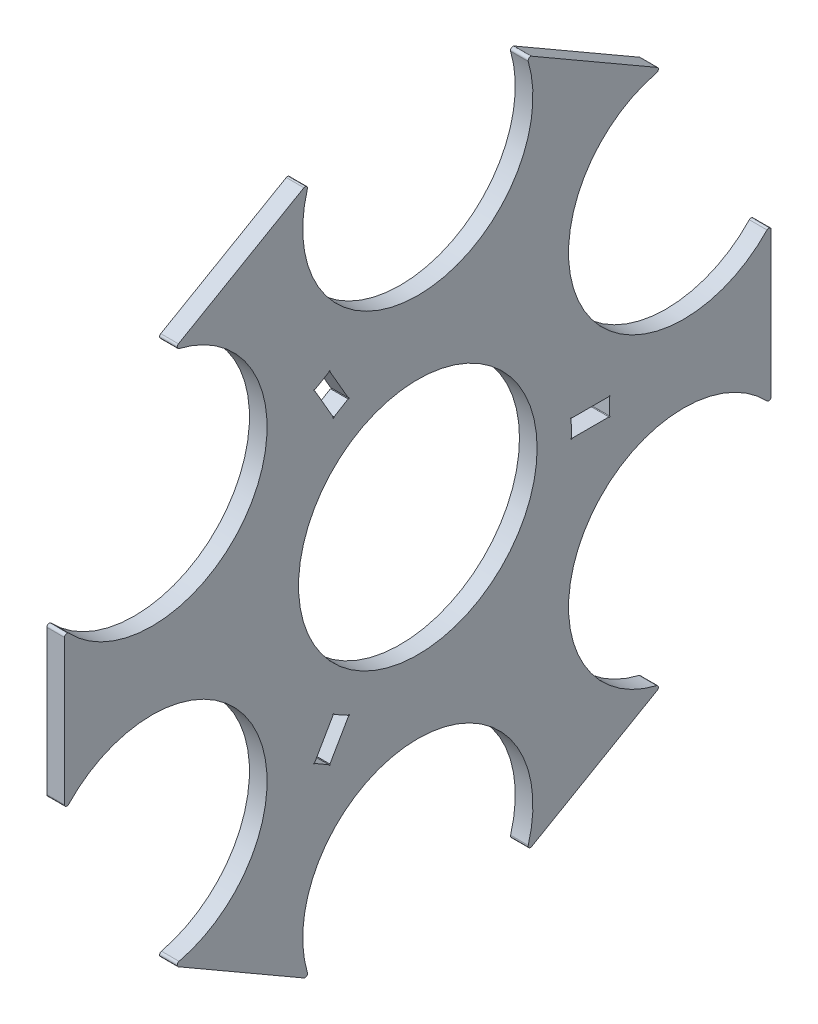
SolidWorks part; units mm, degrees
ref_plane "Front Plane" through (0, 0, 0) normal (0, 0, 1) x (1, 0, 0)
ref_plane "Top Plane" through (0, 0, 0) normal (0, 1, 0) x (1, 0, 0)
ref_plane "Right Plane" through (0, 0, 0) normal (1, 0, 0) x (0, 0, -1)
sketch "Sketch2" plane through (0, 0, 0) normal (1, 0, 0) x (0, 0, -1)
  line L0 (35.921, 114.3) -> (-35.921, 114.3) construction
  line L1 (81.0262, 88.2585) -> (35.921, 114.3)
  line L2 (116.9472, -26.0415) -> (116.9472, 26.0415)
  line L3 (35.921, -114.3) -> (81.0262, -88.2585)
  line L4 (-81.0262, -88.2585) -> (-35.921, -114.3)
  line L5 (-116.9472, 26.0415) -> (-116.9472, -26.0415)
  line L6 (-35.921, 114.3) -> (-81.0262, 88.2585)
  circle A0 centre (0, 0) radius 101.6 construction
  arc A1 (-35.921, 114.3) -> (35.921, 114.3) centre (0, 101.6) ccw
  arc A2 (81.0262, 88.2585) -> (116.9472, 26.0415) centre (87.9882, 50.8) ccw
  arc A3 (116.9472, -26.0415) -> (81.0262, -88.2585) centre (87.9882, -50.8) ccw
  arc A4 (35.921, -114.3) -> (-35.921, -114.3) centre (0, -101.6) ccw
  arc A5 (-81.0262, -88.2585) -> (-116.9472, -26.0415) centre (-87.9882, -50.8) ccw
  arc A6 (-116.9472, 26.0415) -> (-81.0262, 88.2585) centre (-87.9882, 50.8) ccw
  circle A7 centre (0, 0) radius 39.4875
  point P23 (0, 0)
  point P34 (0, 0)
  dimension "D1" = 203.2
  dimension "D2" = 114.3
  dimension "D3" = 76.2
  dimension "D6" = 78.9749
  dimension "D4" = 6
  dimension "D5" = 6
extrude "Boss-Extrude1" add sketch "Sketch2" along normal blind 5.842
fillet "Fillet1" radius 0.7937 12 edges at (2.921, -114.3, 35.921) (2.921, -114.3, -35.921) (2.921, -88.2585, -81.0262) (2.921, -26.0415, -116.9472) (2.921, 88.2585, -81.0262) (2.921, 26.0415, -116.9472) (2.921, -88.2585, 81.0262) (2.921, -26.0415, 116.9472) (2.921, 26.0415, 116.9472) (2.921, 88.2585, 81.0262) (2.921, 114.3, -35.921) (2.921, 114.3, 35.921)
sketch "Sketch6" plane through (5.842, 0, 0) normal (1, 0, 0) x (0, 0, -1)
  line L0 (0, 0) -> (-58.4736, 101.2793) construction
  line L1 (-37.7084, 113.2681) -> (-79.2388, 89.2905) construction
  line L2 (-28.575, 49.4934) -> (-22.225, 38.4948) construction
  line L3 (-23.0045, 45.6869) -> (-29.0967, 56.239)
  line L4 (-28.0045, 42.6631) -> (-34.156, 53.318)
  line L5 (-34.0834, 53.589) -> (-29.3678, 56.3116)
  line L6 (-27.7354, 42.594) -> (-23.075, 45.4123)
  line L8 (2.5297, 1.4605) -> (-55.9439, 102.7398) construction
  line L9 (-2.5297, -1.4605) -> (-61.0033, 99.8188) construction
  arc A0 (-29.0967, 56.239) -> (-29.3678, 56.3116) centre (-29.1959, 56.4108) ccw
  arc A1 (-23.075, 45.4123) -> (-23.0045, 45.6869) centre (-22.9052, 45.515) ccw
  arc A2 (-28.0045, 42.6631) -> (-27.7354, 42.594) centre (-27.9052, 42.4913) ccw
  arc A3 (-34.0834, 53.589) -> (-34.156, 53.318) centre (-34.2552, 53.4898) ccw
  point P8 (-25.4, 43.9941)
  point P12 (-25.4052, 44.0032)
  point P28 (0, 0)
  dimension "D8" = 0.3969
  dimension "D9" = 0.3969
  dimension "D10" = 0.3969
  dimension "D11" = 0.3969
  dimension "D1" = 12.7
  dimension "D2" = 12.5814
  dimension "D5" = 12.7
  dimension "D6" = 50.8
  dimension "D3" = 2.921
  dimension "D4" = 2.921
extrude "Cut-Extrude2" cut sketch "Sketch6" against normal through all
pattern_circular "CirPattern2" count 3 every 120 about axis through (0, 0, 0) along (1, 0, 0) of "Cut-Extrude2"
